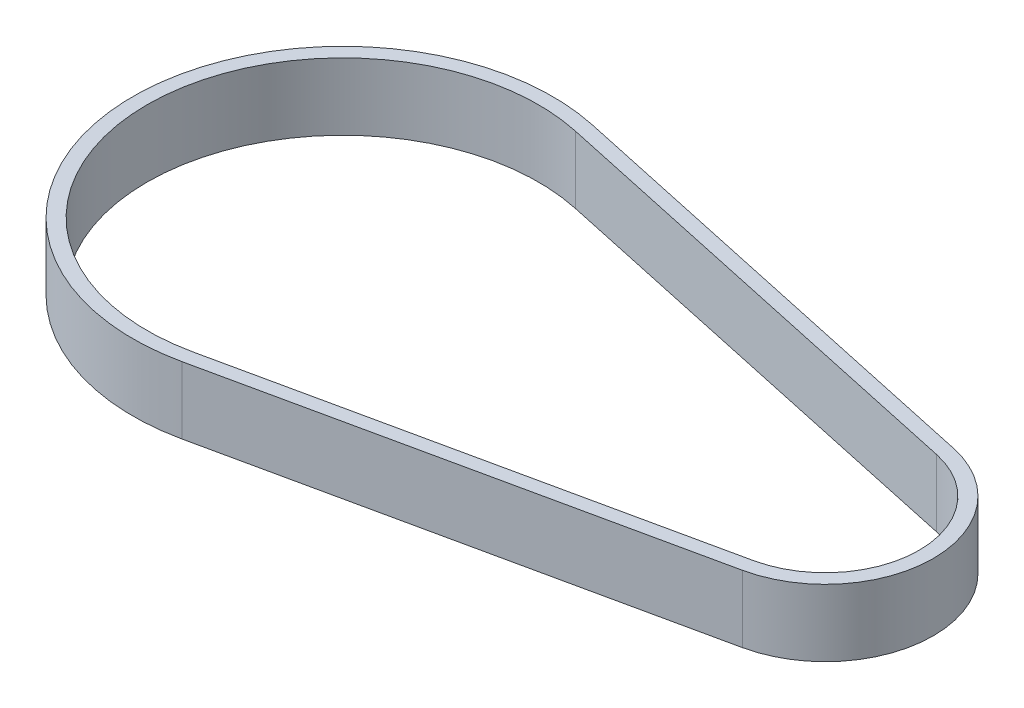
SolidWorks part; units mm, degrees
ref_plane "Front" through (0, 0, 0) normal (0, 0, 1) x (1, 0, 0)
ref_plane "Top" through (0, 0, 0) normal (0, 1, 0) x (1, 0, 0)
ref_plane "Right" through (0, 0, 0) normal (1, 0, 0) x (0, 0, -1)
sketch "Sketch1" plane through (0, 0, 0) normal (0, 1, 0) x (1, 0, 0)
  line L0 (16.53, 76.5353) -> (188.5078, 39.3917)
  line L1 (16.53, -76.5353) -> (188.5078, -39.3917)
  line L2 (15.4111, -71.3547) -> (187.3889, -34.2112)
  line L3 (15.4111, 71.3547) -> (187.3889, 34.2112)
  arc A0 (188.5078, -39.3917) -> (188.5078, 39.3917) centre (180, 0) ccw
  arc A1 (16.53, 76.5353) -> (16.53, -76.5353) centre (0, 0) ccw
  arc A2 (15.4111, 71.3547) -> (15.4111, -71.3547) centre (0, 0) ccw
  arc A3 (187.3889, -34.2112) -> (187.3889, 34.2112) centre (180, 0) ccw
  dimension "D1" = 73
  dimension "D2" = 35
  dimension "D3" = 180
  dimension "D4" = 5.3
extrude "Boss-Extrude1" add sketch "Sketch1" along normal blind 25
